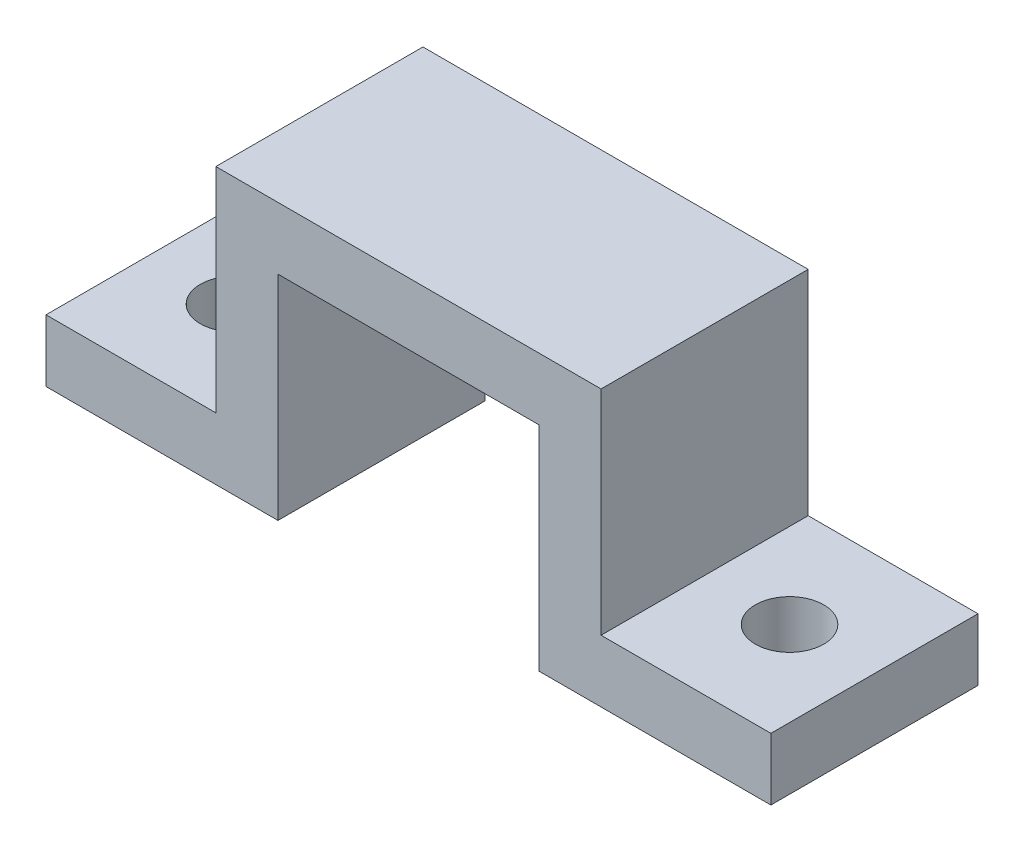
SolidWorks part; units mm, degrees
ref_plane "Front Plane" through (0, 0, 0) normal (0, 0, 1) x (1, 0, 0)
ref_plane "Top Plane" through (0, 0, 0) normal (0, 1, 0) x (1, 0, 0)
ref_plane "Right Plane" through (0, 0, 0) normal (1, 0, 0) x (0, 0, -1)
sketch "Sketch1" plane through (0, 0, 0) normal (0, 0, 1) x (1, 0, 0)
  line L0 (-6.3, -5.15) -> (-17.5, -5.15)
  line L1 (-6.3, 5.15) -> (6.3, 5.15)
  line L2 (-6.3, 5.15) -> (-6.3, -5.15)
  line L3 (-6.3, -5.15) -> (6.3, -5.15)
  line L4 (6.3, 5.15) -> (6.3, -5.15)
  line L5 (-6.3, 5.15) -> (6.3, -5.15) construction
  line L6 (-6.3, -5.15) -> (6.3, 5.15) construction
  line L7 (-17.5, -5.15) -> (-17.5, -2.15)
  line L8 (-17.5, -2.15) -> (-9.3, -2.15)
  line L9 (-9.3, -2.15) -> (-9.3, 8.15)
  line L10 (-9.3, 8.15) -> (9.3, 8.15)
  line L11 (9.3, 8.15) -> (9.3, -2.15)
  line L12 (9.3, -2.15) -> (17.5, -2.15)
  line L13 (17.5, -2.15) -> (17.5, -5.15)
  line L14 (17.5, -5.15) -> (6.3, -5.15)
  point P0 (0, 0)
  dimension "D1" = 12.6
  dimension "D2" = 10.3
  dimension "D3" = 3
  dimension "D4" = 3
  dimension "D5" = 3
  dimension "D6" = 3
  dimension "D7" = 11.2
extrude "Boss-Extrude1" add sketch "Sketch1" along normal blind 10 contours L14 L13 L12 L11 L10 L9 L8 L7 L0 L2 L1 L4
sketch "Sketch2" plane through (0, -2.15, 0) normal (0, 1, 0) x (1, 0, 0)
  line L0 (0, 0) -> (0, -10) construction
  line L1 (-9.3, -10) -> (9.3, -10) construction
  line L2 (-13.4, -5) -> (13.4, -5)
  line L5 (17.5, -10) -> (17.5, 0) construction
  circle A0 centre (13.4, -5) radius 1.65
  circle A1 centre (-13.4, -5) radius 1.65
  point P8 (0, -5)
  dimension "D2" = 3.3
  dimension "D1" = 4.1
extrude "Cut-Extrude1" cut sketch "Sketch2" against normal up to surface (3 mm away) up to face at (11.9, -5.15, 5)
